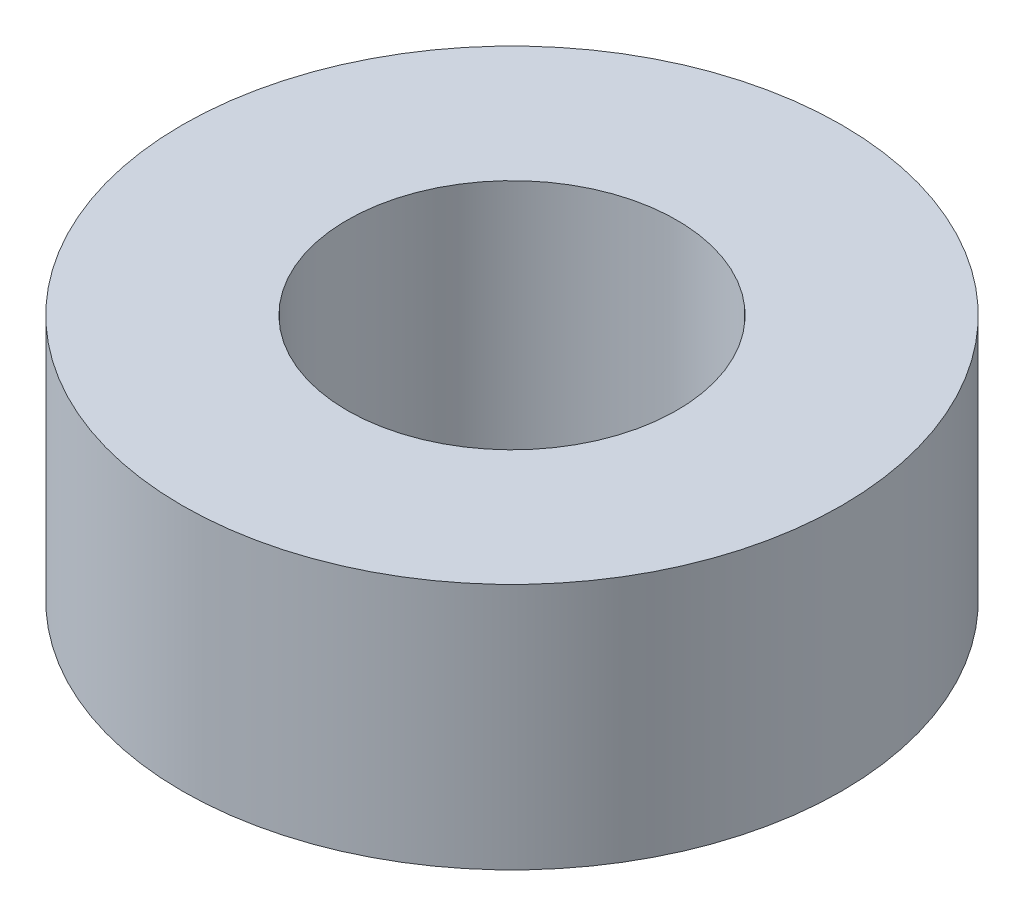
SolidWorks part; units mm, degrees
material "1023 碳钢板 (SS)"
ref_plane "前视基准面" through (0, 0, 0) normal (0, 0, 1) x (1, 0, 0)
ref_plane "上视基准面" through (0, 0, 0) normal (0, 1, 0) x (1, 0, 0)
ref_plane "右视基准面" through (0, 0, 0) normal (1, 0, 0) x (0, 0, -1)
other "Configuration Table"
sketch "草图1" plane through (0, 0, 0) normal (0, 1, 0) x (1, 0, 0)
  circle A0 centre (0, 0) radius 6
  circle A1 centre (0, 0) radius 3
  dimension "D1" = 12
  dimension "D2" = 6
extrude "凸台-拉伸1" add sketch "草图1" along normal blind 4.5
